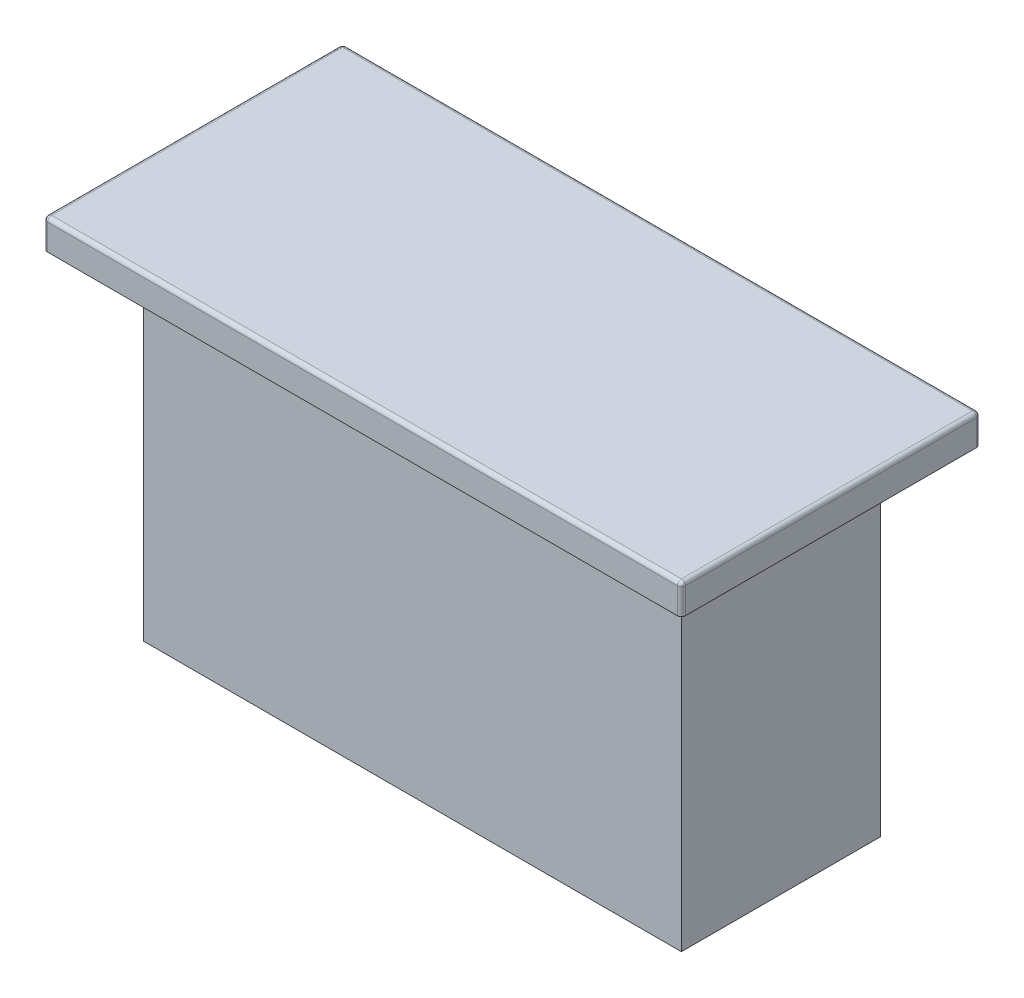
SolidWorks part; units mm, degrees
ref_plane "Front Plane" through (0, 0, 0) normal (0, 0, 1) x (1, 0, 0)
ref_plane "Top Plane" through (0, 0, 0) normal (0, 1, 0) x (1, 0, 0)
ref_plane "Right Plane" through (0, 0, 0) normal (1, 0, 0) x (0, 0, -1)
sketch "Sketch1" plane through (0, 0, 0) normal (0, 1, 0) x (1, 0, 0)
  line L0 (-31.8, 14.8) -> (-31.8, 0.2) construction
  line L1 (0, 0) -> (-32, 0)
  line L2 (0, 0) -> (0, 15)
  line L3 (0, 15) -> (-32, 15)
  line L4 (-32, 0) -> (-32, 15)
  line L5 (-31.8, 0.2) -> (-0.2, 0.2) construction
  line L6 (-0.2, 0.2) -> (-0.2, 14.8) construction
  line L7 (-0.2, 14.8) -> (-31.8, 14.8) construction
  line L8 (-32, 0.2) -> (-32, 14.8) construction
  line L9 (-31.8, 15) -> (-0.2, 15) construction
  line L10 (0, 14.8) -> (0, 0.2) construction
  line L11 (-0.2, 0) -> (-31.8, 0) construction
  line L12 (-31.8, 14.8) -> (-31.8, 0.2) construction
  line L13 (-31.8, 0.2) -> (-0.2, 0.2) construction
  line L14 (-0.2, 0.2) -> (-0.2, 14.8) construction
  line L15 (-0.2, 14.8) -> (-31.8, 14.8) construction
  arc A0 (-31.8, 15) -> (-32, 14.8) centre (-31.8, 14.8) ccw construction
  arc A1 (0, 14.8) -> (-0.2, 15) centre (-0.2, 14.8) ccw construction
  arc A2 (-0.2, 0) -> (0, 0.2) centre (-0.2, 0.2) ccw construction
  arc A3 (-32, 0.2) -> (-31.8, 0) centre (-31.8, 0.2) ccw construction
  dimension "D1" = 15
  dimension "D2" = 32
extrude "Boss-Extrude1" add sketch "Sketch1" along normal blind 1.5
fillet "Fillet2" radius 0.2 8 edges at (-16, 1.5, 0) (-32, 1.5, -7.5) (-16, 1.5, -15) (0, 1.5, -7.5) (-32, 0.75, -15) (-32, 0.75, 0) (0, 0.75, -15) (0, 0.75, 0)
sketch "Sketch2" plane through (0, 1.5, 0) normal (0, 1, 0) x (1, 0, 0)
  line L8 (-29.5, 12.5) -> (-29.5, 2.5)
  line L9 (-29.5, 2.5) -> (-2.5, 2.5)
  line L10 (-2.5, 2.5) -> (-2.5, 12.5)
  line L11 (-2.5, 12.5) -> (-29.5, 12.5)
  line L12 (-29.5, 12.5) -> (-29.5, 2.5)
  line L13 (-29.5, 2.5) -> (-2.5, 2.5)
  line L14 (-2.5, 2.5) -> (-2.5, 12.5)
  line L15 (-2.5, 12.5) -> (-29.5, 12.5)
  dimension "D1" = 2.3
extrude "Boss-Extrude2" add sketch "Sketch2" against normal blind 18.5 contours L12 L13 L14 L15
